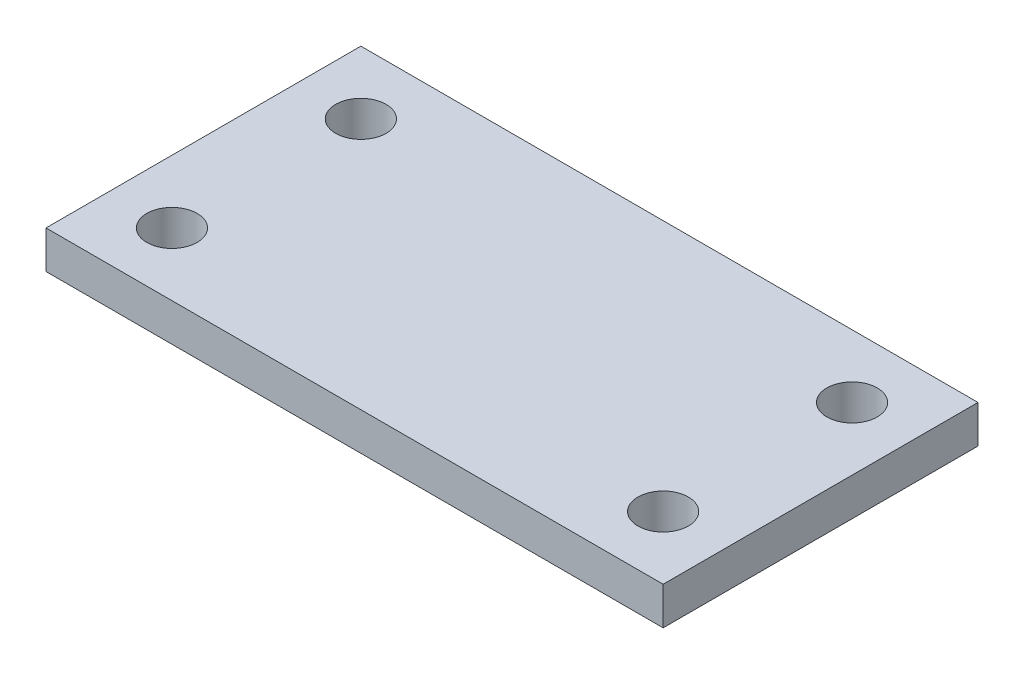
SolidWorks part; units mm, degrees
ref_plane "Front Plane" through (0, 0, 0) normal (0, 0, 1) x (1, 0, 0)
ref_plane "Top Plane" through (0, 0, 0) normal (0, 1, 0) x (1, 0, 0)
ref_plane "Right Plane" through (0, 0, 0) normal (1, 0, 0) x (0, 0, -1)
sketch "Sketch2" plane through (0, 0, 0) normal (0, 1, 0) x (1, 0, 0)
  line L0 (17.3009, 13.9336) -> (17.3009, -11.0664)
  line L1 (17.3009, -11.0664) -> (-31.6991, -11.0664)
  line L2 (-31.6991, -11.0664) -> (-31.6991, 13.9336)
  line L3 (-31.6991, 13.9336) -> (17.3009, 13.9336)
  dimension "D1" = 49
  dimension "D2" = 25
extrude "Boss-Extrude1" add sketch "Sketch2" along normal blind 3 contours L1 L2 L3 L0
sketch "Sketch3" plane through (0, 3, 0) normal (0, 1, 0) x (1, 0, 0)
  line L0 (-31.6991, 13.9336) -> (17.3009, 13.9336) construction
  line L2 (17.3009, 13.9336) -> (17.3009, -11.0664) construction
  line L3 (-31.6991, -11.0664) -> (-31.6991, 13.9336) construction
  line L4 (17.3009, -11.0664) -> (-31.6991, -11.0664) construction
  circle A0 centre (-26.6991, 8.9336) radius 2
  circle A1 centre (-26.6991, -6.0664) radius 2
  circle A2 centre (12.3009, 8.9336) radius 2
  circle A3 centre (12.3009, -6.0664) radius 2
  dimension "D1" = 4
  dimension "D2" = 4
  dimension "D3" = 4
  dimension "D4" = 4
  dimension "D5" = 5
  dimension "D6" = 5
  dimension "D7" = 5
  dimension "D8" = 5
  dimension "D9" = 5
  dimension "D10" = 5
  dimension "D11" = 5
  dimension "D12" = 5
extrude "Cut-Extrude1" cut sketch "Sketch3" against normal blind 3
